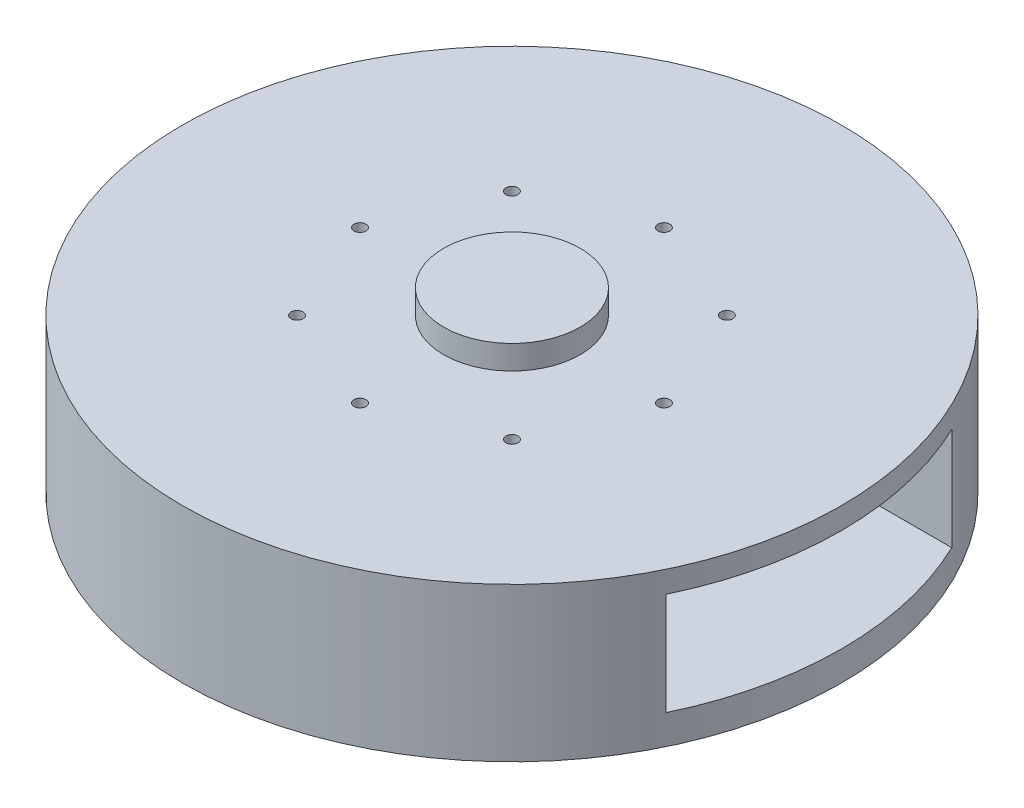
SolidWorks part; units mm, degrees
ref_plane "前视基准面" through (0, 0, 0) normal (0, 0, 1) x (1, 0, 0)
ref_plane "上视基准面" through (0, 0, 0) normal (0, 1, 0) x (1, 0, 0)
ref_plane "右视基准面" through (0, 0, 0) normal (1, 0, 0) x (0, 0, -1)
other "Configuration Table"
sketch "草图1" plane through (0, 0, 0) normal (0, 1, 0) x (1, 0, 0)
  circle A0 centre (0, 0) radius 96.5
extrude "凸台-拉伸1" add sketch "草图1" along normal blind 45
sketch "草图2" plane through (0, 0, 0) normal (0, -1, 0) x (-1, 0, 0)
  circle A0 centre (0, 0) radius 48.25
extrude "切除-拉伸1" cut sketch "草图2" against normal blind 42.3
sketch "草图3" plane through (0, 0, 0) normal (1, 0, 0) x (0, 0, -1)
  line L0 (0, 24.75) -> (0, -24.75) construction
  line L1 (41.8102, 38.652) -> (-41.8102, 38.652)
  line L2 (41.8102, 38.652) -> (41.8102, 8.652)
  line L3 (41.8102, 8.652) -> (-41.8102, 8.652)
  line L4 (-41.8102, 38.652) -> (-41.8102, 8.652)
  line L5 (41.8102, 38.652) -> (-41.8102, 8.652) construction
  line L6 (41.8102, 8.652) -> (-41.8102, 38.652) construction
  point P0 (0, 23.652)
  dimension "D1" = 30
extrude "切除-拉伸2" cut sketch "草图3" against normal mid plane 1000
sketch3d "3D草图2"
  point P0 (-3.2601, 20.8808, 1.2283)
  point P2 (-3.2601, 20.8808, 1.2283)
  point P3 (-3.2601, 20.8808, 1.2283)
sketch "草图4" plane through (0, 45, 0) normal (0, 1, 0) x (1, 0, 0)
  circle A0 centre (0, 0) radius 20
sketch "草图5" plane through (0, 45, 0) normal (0, 1, 0) x (1, 0, 0)
  circle A0 centre (0, 0) radius 20
extrude "凸台-拉伸2" add sketch "草图5" along normal blind 7
ref_plane "基准面1" through (-86.9721, 38.652, -41.8102) normal (0, 1, 0) x (1, 0, 0)
sketch "草图7" plane through (0, 0, 0) normal (0, -1, 0) x (1, 0, 0)
  line L0 (-96.4334, 3.5856) -> (96.5, 0)
  circle A0 centre (0, 0) radius 96.5 construction
sketch "草图8" plane through (0, 42.3, 0) normal (0, -1, 0) x (-1, 0, 0)
  line L0 (0, -44.5) -> (0, 44.5) construction
  circle A0 centre (0, 0) radius 44.5 construction
  circle A1 centre (0, -44.5) radius 1.75
  circle A2 centre (-31.4663, -31.4663) radius 1.75
  circle A3 centre (-44.5, 0) radius 1.75
  circle A4 centre (-31.4663, 31.4663) radius 1.75
  circle A5 centre (0, 44.5) radius 1.75
  circle A6 centre (31.4663, 31.4663) radius 1.75
  circle A7 centre (44.5, 0) radius 1.75
  circle A8 centre (31.4663, -31.4663) radius 1.75
  point P22 (0, 0)
  dimension "D1" = 3.5
  dimension "D2" = 8
extrude "切除-拉伸3" cut sketch "草图8" against normal through all
